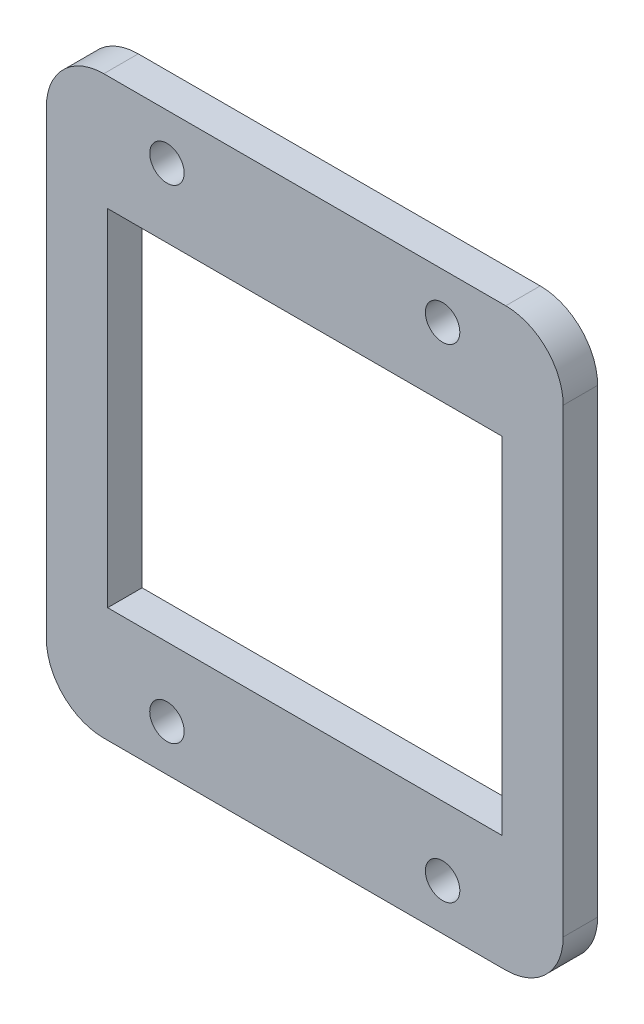
SolidWorks part; units mm, degrees
ref_plane "前视基准面" through (0, 0, 0) normal (0, 0, 1) x (1, 0, 0)
ref_plane "上视基准面" through (0, 0, 0) normal (0, 1, 0) x (1, 0, 0)
ref_plane "右视基准面" through (0, 0, 0) normal (1, 0, 0) x (0, 0, -1)
other "Configuration Table"
sketch "草图1" plane through (0, 0, 0) normal (0, 0, 1) x (1, 0, 0)
  line L0 (22.5, 0) -> (22.5, 40.1) construction
  line L1 (0, 0) -> (45, 0)
  line L2 (0, 0) -> (0, 50.1)
  line L3 (0, 50.1) -> (45, 50.1)
  line L4 (45, 0) -> (45, 50.1)
  line L5 (5.3348, 40.1) -> (39.6652, 40.1)
  line L6 (5.3348, 40.1) -> (5.3348, 10)
  line L7 (5.3348, 10) -> (39.6652, 10)
  line L8 (39.6652, 40.1) -> (39.6652, 10)
  line L9 (0, 25.05) -> (5.3348, 25.05) construction
  circle A0 centre (10.5, 46.1) radius 1.5
  circle A1 centre (34.5, 46.1) radius 1.5
  circle A2 centre (34.5, 4) radius 1.5
  circle A3 centre (10.5, 4) radius 1.5
  dimension "D5" = 3
  dimension "D6" = 24
  dimension "D7" = 4
  dimension "D1" = 50.1
  dimension "D2" = 45
  dimension "D3" = 34.3304
  dimension "D4" = 10
extrude "凸台-拉伸1" add sketch "草图1" along normal blind 3
fillet "圆角1" radius 5 4 edges at (0, 50.1, 1.5) (0, 0, 1.5) (45, 0, 1.5) (45, 50.1, 1.5)
